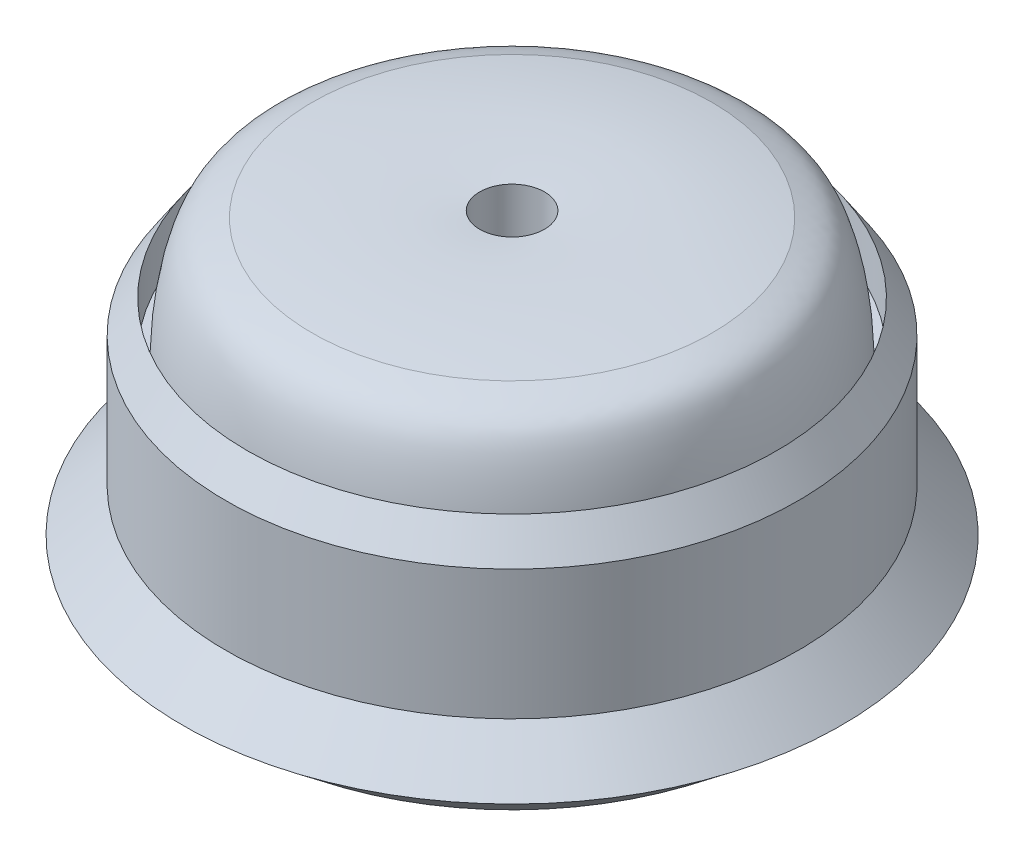
SolidWorks part; units mm, degrees
ref_plane "前视基准面" through (0, 0, 0) normal (0, 0, 1) x (1, 0, 0)
ref_plane "上视基准面" through (0, 0, 0) normal (0, 1, 0) x (1, 0, 0)
ref_plane "右视基准面" through (0, 0, 0) normal (1, 0, 0) x (0, 0, -1)
sketch "草图1" plane through (0, 0, 0) normal (0, 0, 1) x (1, 0, 0)
  line L0 (0, 0) -> (0, 30) construction
  line L1 (0, 0) -> (30, 0) construction
  line L2 (3, 30) -> (3, 25.265)
  line L3 (3, 25.265) -> (5.5, 25.265)
  line L4 (5.5, 25.265) -> (5.5, 28)
  line L5 (5.5, 28) -> (18.5, 28)
  line L6 (18.5, 28) -> (18.5, 17)
  line L7 (18.5, 17) -> (22.5, 17)
  line L8 (22.5, 17) -> (22.5, 0)
  line L9 (22.5, 0) -> (25.5, 0)
  line L10 (30.5, 4) -> (26.5, 8)
  line L11 (26.5, 8) -> (26.5, 20)
  line L12 (26.5, 20) -> (24.5, 23)
  line L13 (24.5, 23) -> (24.5, 18.4217)
  line L14 (24.5, 18.4217) -> (23.7, 18.4217)
  line L15 (25.5, 0) -> (30.5, 4)
  line L16 (26.5, 20) -> (24.5, 20) construction
  spline S0 degree 2 poles (3, 30) (10.804, 30.6291) (18.5, 29.4293) knots 0 0 0 1 1 1
  spline S1 degree 3 poles (18.5, 29.4293) (20.5119, 28.7061) (22.7386, 27.8724) (23.7839, 20.5596) (23.7, 17.2047) knots 0 0 0 0 0.382453 1 1 1 1
  point P21 (23.7, 17.2047)
  point P24 (19.9681, 27.9962)
  point P26 (20.0974, 27.829)
  point P28 (20.4573, 28)
  point P29 (17.2193, 29.3635)
  point P30 (17.3737, 29.5918)
  point P31 (21.7027, 27.6568)
  point P32 (18.5, 29.4293)
  dimension "D1" = 30
  dimension "D2" = 30
  dimension "D3" = 8
  dimension "D4" = 3
  dimension "D5" = 22.5
  dimension "D6" = 4
  dimension "D7" = 3
  dimension "D8" = 8
  dimension "D9" = 4
  dimension "D10" = 12
  dimension "D11" = 2
  dimension "D12" = 3
  dimension "D13" = 0.8
  dimension "D14" = 17
  dimension "D15" = 11
  dimension "D16" = 13
  dimension "D17" = 2.5
revolve "旋转1" add sketch "草图1" angle 360 about L0
